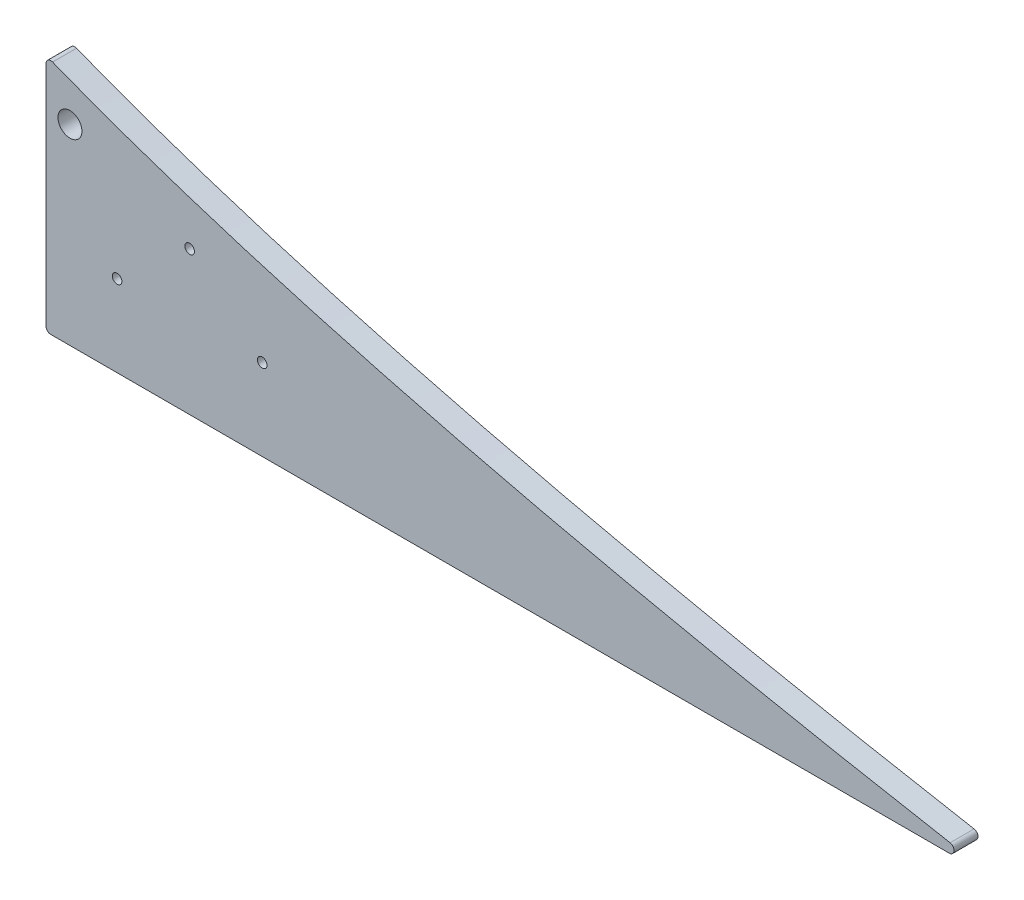
SolidWorks part; units mm, degrees
ref_plane "Front Plane" through (0, 0, 0) normal (0, 0, 1) x (1, 0, 0)
ref_plane "Top Plane" through (0, 0, 0) normal (0, 1, 0) x (1, 0, 0)
ref_plane "Right Plane" through (0, 0, 0) normal (1, 0, 0) x (0, 0, -1)
sketch "Sketch1" plane through (0, 0, 0) normal (0, 0, 1) x (1, 0, 0)
  line L0 (0, 0) -> (0, 127)
  line L3 (508, 0) -> (0, 0)
  circle A0 centre (12.7, 101.6) radius 6.35
  spline S0 degree 2 poles (0, 127) (169.847, 59.0807) (508, 0) knots 0 0 0 1 1 1
  point P9 (12.2289, 209.6921)
  dimension "D3" = 12.7
  dimension "D1" = 127
  dimension "D2" = 508
  dimension "D4" = 12.7
  dimension "D5" = 25.4
extrude "Boss-Extrude1" add sketch "Sketch1" along normal blind 12.7
fillet "Fillet1" radius 2.54 1 edges at (0, 127, 6.35)
fillet "Fillet2" radius 2.54 2 edges at (0, 0, 6.35) (508, 0, 6.35)
sketch "Sketch2" plane through (0, 0, 12.7) normal (0, 0, 1) x (1, 0, 0)
  line L0 (0, 123.2566) -> (0, 2.54) construction
  line L1 (2.54, 0) -> (479.0999, 0) construction
  circle A0 centre (76.2, 76.2) radius 2.54
  circle A1 centre (37.7088, 43.2003) radius 2.54
  circle A2 centre (114.6912, 43.2003) radius 2.54
  dimension "D1" = 5.08
  dimension "D2" = 5.08
  dimension "D3" = 5.08
  dimension "D4" = 38.4912
  dimension "D5" = 32.9997
  dimension "D6" = 38.4912
  dimension "D7" = 32.9997
  dimension "D8" = 76.2
  dimension "D9" = 76.2
extrude "Cut-Extrude1" cut sketch "Sketch2" against normal blind 203.2
